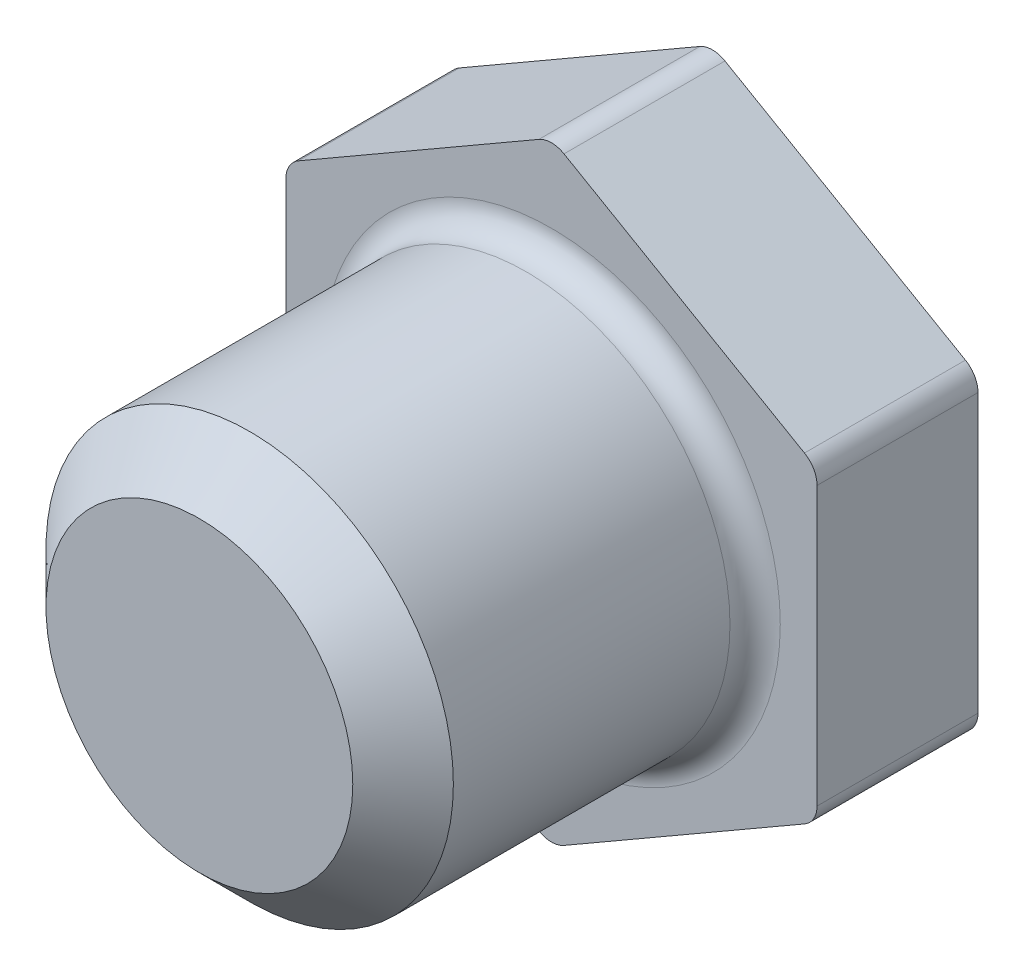
SolidWorks part; units mm, degrees
ref_plane "Front Plane" through (0, 0, 0) normal (0, 0, 1) x (1, 0, 0)
ref_plane "Top Plane" through (0, 0, 0) normal (0, 1, 0) x (1, 0, 0)
ref_plane "Right Plane" through (0, 0, 0) normal (1, 0, 0) x (0, 0, -1)
sketch "Sketch1" plane through (0, 0, 0) normal (0, 0, 1) x (1, 0, 0)
  line L0 (5.2813, 3.0492) -> (0, 6.0983)
  line L7 (0, 8.35) -> (-7.2313, 4.175)
  line L8 (-7.2313, 4.175) -> (-7.2313, -4.175)
  line L9 (-7.2313, -4.175) -> (0, -8.35)
  line L10 (0, -8.35) -> (7.2313, -4.175)
  line L11 (7.2313, -4.175) -> (7.2313, 4.175)
  line L12 (7.2313, 4.175) -> (0, 8.35)
  line L13 (0, 6.0983) -> (-5.2813, 3.0492)
  line L14 (-5.2813, 3.0492) -> (-5.2813, -3.0492)
  line L15 (-5.2813, -3.0492) -> (0, -6.0983)
  line L16 (0, -6.0983) -> (5.2813, -3.0492)
  line L17 (5.2813, -3.0492) -> (5.2813, 3.0492)
  circle A0 centre (0, 0) radius 8.35 construction
  dimension "D1" = 16.7
  dimension "D2" = 1.95
extrude "Boss-Extrude1" add sketch "Sketch1" along normal blind 3.2 contours L0 L13 L14 L15 L16 L17
sketch "Sketch2" plane through (0, 0, 3.2) normal (0, 0, 1) x (1, 0, 0)
  circle A0 centre (0, 0) radius 4.05
  dimension "D1" = 8.1
extrude "Boss-Extrude2" add sketch "Sketch2" along normal blind 7
fillet "Fillet1" radius 0.5 7 edges at (4.05, 0, 3.2) (-5.2813, 3.0492, 1.6) (-5.2813, -3.0492, 1.6) (0, -6.0983, 1.6) (5.2813, -3.0492, 1.6) (5.2813, 3.0492, 1.6) (0, 6.0983, 1.6)
chamfer "Chamfer1" distance 1 angle 45 1 edges at (4.05, 0, 10.2)
